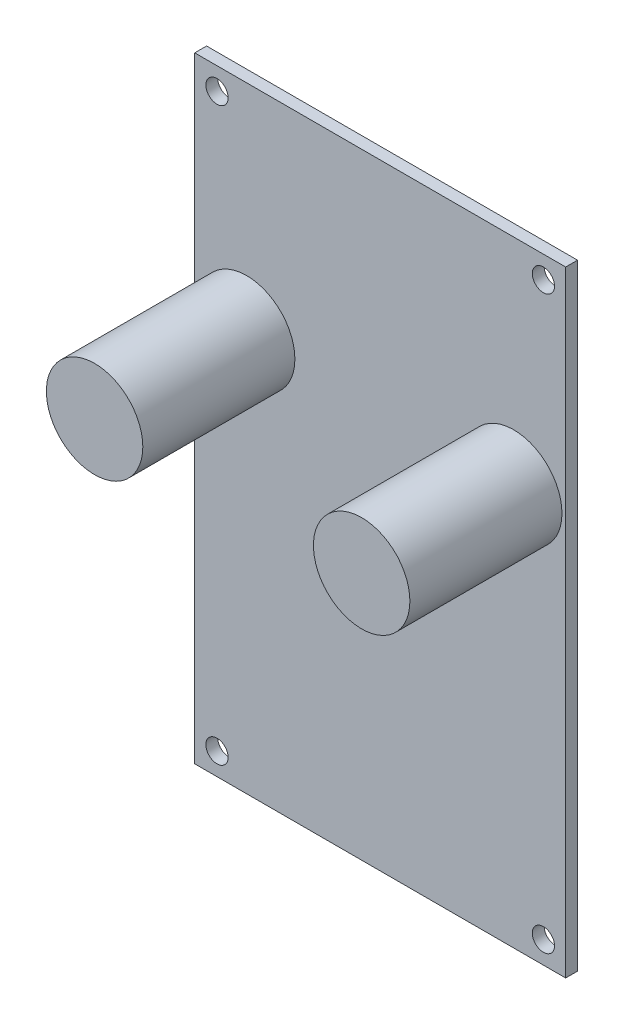
SolidWorks part; units mm, degrees
ref_plane "Plan de face" through (0, 0, 0) normal (0, 0, 1) x (1, 0, 0)
ref_plane "Plan de dessus" through (0, 0, 0) normal (0, 1, 0) x (1, 0, 0)
ref_plane "Plan de droite" through (0, 0, 0) normal (1, 0, 0) x (0, 0, -1)
sketch "Esquisse1" plane through (0, 0, 0) normal (0, 0, 1) x (1, 0, 0)
  line L1 (0, 0) -> (50, 0)
  line L2 (0, 0) -> (0, -83)
  line L3 (0, -83) -> (50, -83)
  line L4 (50, 0) -> (50, -83)
  circle A0 centre (3, -3) radius 1.5
  circle A1 centre (47, -3) radius 1.5
  circle A2 centre (47, -80) radius 1.5
  circle A3 centre (3, -80) radius 1.5
  dimension "D3" = 3
  dimension "D4" = 3
  dimension "D5" = 3
  dimension "D6" = 3
  dimension "D1" = 50
  dimension "D2" = 83
  dimension "D7" = 44
  dimension "D8" = 77
  dimension "D9" = 77
  dimension "D10" = 44
  dimension "D11" = 77
  dimension "D12" = 44
  dimension "D13" = 3
  dimension "D14" = 3
extrude "Boss.-Extru.1" add sketch "Esquisse1" along normal blind 1.6
sketch "Esquisse2" plane through (0, 0, 1.6) normal (0, 0, 1) x (1, 0, 0)
  line L0 (50, 0) -> (0, 0) construction
  line L2 (0, 0) -> (0, -83) construction
  line L3 (50, -83) -> (50, 0) construction
  circle A0 centre (7, -29) radius 6.5
  circle A1 centre (43, -29) radius 6.5
  point P8 (0, -30.7962)
  dimension "D1" = 13
  dimension "D2" = 13
  dimension "D3" = 29
  dimension "D4" = 29
  dimension "D5" = 7
  dimension "D6" = 7
extrude "Boss.-Extru.2" add sketch "Esquisse2" along normal blind 20.5
